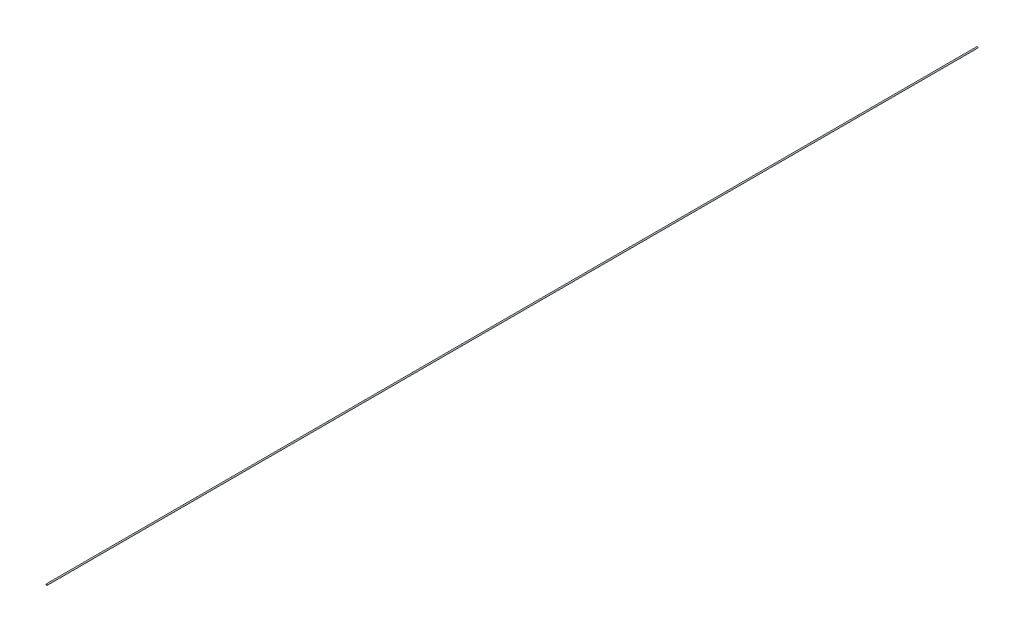
SolidWorks part; units mm, degrees
ref_plane "Front Plane" through (0, 0, 0) normal (0, 0, 1) x (1, 0, 0)
ref_plane "Top Plane" through (0, 0, 0) normal (0, 1, 0) x (1, 0, 0)
ref_plane "Right Plane" through (0, 0, 0) normal (1, 0, 0) x (0, 0, -1)
sketch "Sketch1" plane through (0, 0, 0) normal (0, 0, 1) x (1, 0, 0)
  circle A0 centre (0, 0) radius 3.175
  dimension "D1" = 6.35
extrude "Extrude1" add sketch "Sketch1" along normal blind 4572
sketch "Sketch2" plane through (0, 0, 0) normal (0, 0, -1) x (-1, 0, 0)
  point P0 (0, 0)
sketch "Sketch3" plane through (0, 0, 4572) normal (0, 0, 1) x (1, 0, 0)
  point P0 (0, 0)
